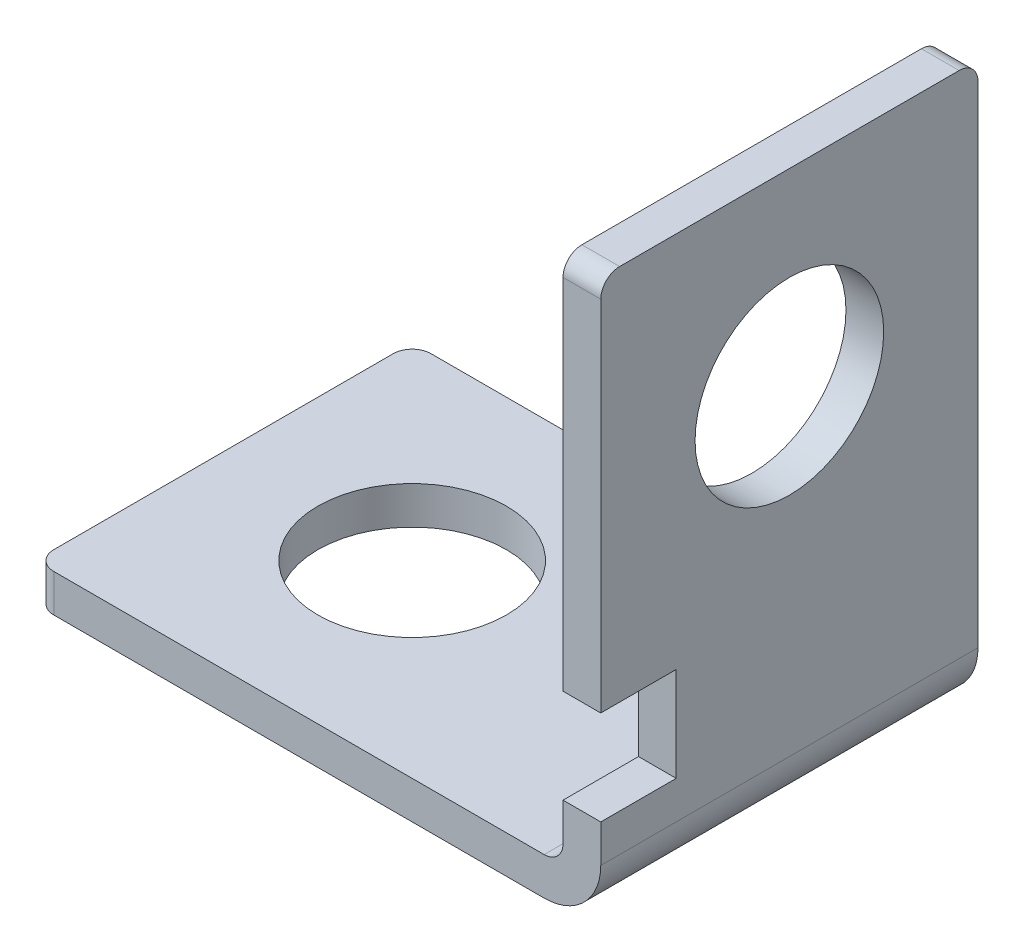
SolidWorks part; units mm, degrees
material "6061 Alloy"
ref_plane "Front Plane" through (0, 0, 0) normal (0, 0, 1) x (1, 0, 0)
ref_plane "Top Plane" through (0, 0, 0) normal (0, 1, 0) x (1, 0, 0)
ref_plane "Right Plane" through (0, 0, 0) normal (1, 0, 0) x (0, 0, -1)
sketch "Sketch1" plane through (0, 0, 0) normal (0, 0, 1) x (1, 0, 0)
  line L0 (0, 0) -> (27, 0)
  line L1 (30, 3) -> (30, 30)
  arc A0 (30, 3) -> (27, 0) centre (27, 3) cw
  point P6 (30, 0)
  dimension "D2" = 3
  dimension "D1" = 30
extrude "Extrude-Thin1" add sketch "Sketch1" along normal blind 20 thin thin type one direction reverse wall 2
sketch "Sketch2" plane through (28, 0, 0) normal (-1, 0, 0) x (0, 0, 1)
  line L0 (0, 3) -> (0, 30) construction
  line L1 (20, 30) -> (0, 30) construction
  line L2 (20, 3) -> (20, 30) construction
  line L3 (20, 5) -> (16, 5)
  line L4 (20, 5) -> (20, 10)
  line L5 (20, 10) -> (16, 10)
  line L6 (16, 5) -> (16, 10)
  circle A0 centre (10, 20) radius 5
  dimension "D1" = 10
  dimension "D2" = 10
  dimension "D3" = 10
  dimension "D4" = 4
  dimension "D5" = 5
  dimension "D6" = 20
extrude "Cut-Extrude1" cut sketch "Sketch2" against normal through all
sketch "Sketch3" plane through (0, 2, 0) normal (0, 1, 0) x (1, 0, 0)
  line L0 (0, -20) -> (0, 0) construction
  line L1 (0, -20) -> (27, -20) construction
  circle A0 centre (10, -10) radius 5
  dimension "D1" = 10
  dimension "D2" = 10
  dimension "D3" = 10
extrude "Cut-Extrude2" cut sketch "Sketch3" against normal through all
fillet "Fillet1" radius 1 4 edges at (0, 1, 0) (0, 1, 20) (29, 30, 20) (29, 30, 0)
